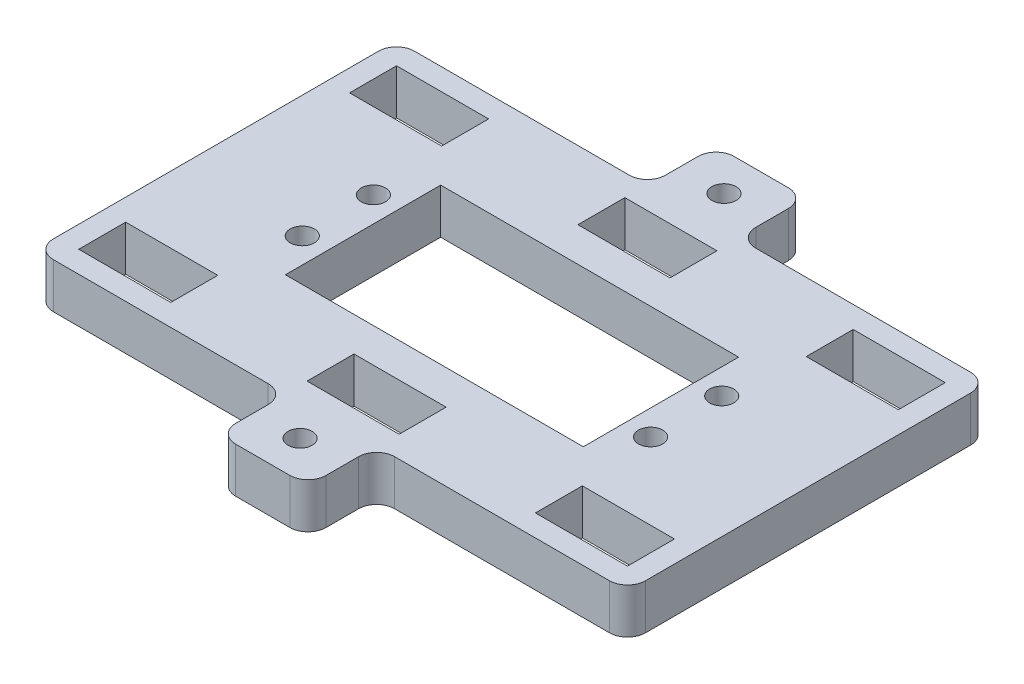
SolidWorks part; units mm, degrees
material "Acrylic (Medium-high impact)"
ref_plane "Front Plane" through (0, 0, 0) normal (0, 0, 1) x (1, 0, 0)
ref_plane "Top Plane" through (0, 0, 0) normal (0, 1, 0) x (1, 0, 0)
ref_plane "Right Plane" through (0, 0, 0) normal (1, 0, 0) x (0, 0, -1)
sketch "Sketch1" plane through (0, 0, 0) normal (0, 1, 0) x (1, 0, 0)
  line L0 (-25.7708, 22.225) -> (-6.35, 22.225) construction
  line L1 (-20.955, -10.922) -> (20.955, -10.922)
  line L2 (-20.955, -10.922) -> (-20.955, 10.922)
  line L3 (-20.955, 10.922) -> (20.955, 10.922)
  line L4 (20.955, -10.922) -> (20.955, 10.922)
  line L5 (-20.955, -10.922) -> (20.955, 10.922) construction
  line L6 (-20.955, 10.922) -> (20.955, -10.922) construction
  line L7 (24.4996, -5) -> (-24.4996, -5) construction
  line L8 (24.4996, -5) -> (24.4996, 5) construction
  line L9 (24.4996, 5) -> (-24.4996, 5) construction
  line L10 (-24.4996, -5) -> (-24.4996, 5) construction
  line L11 (24.4996, -5) -> (-24.4996, 5) construction
  line L12 (24.4996, 5) -> (-24.4996, -5) construction
  line L13 (41.6458, -25.4) -> (-41.6458, -25.4) construction
  line L14 (41.6458, -25.4) -> (41.6458, 25.4)
  line L15 (41.6458, 25.4) -> (-41.6458, 25.4) construction
  line L16 (-41.6458, -25.4) -> (-41.6458, 25.4)
  line L17 (41.6458, -25.4) -> (-41.6458, 25.4) construction
  line L18 (41.6458, 25.4) -> (-41.6458, -25.4) construction
  line L19 (-38.4708, 22.225) -> (-25.7708, 22.225) construction
  line L20 (-38.4708, 22.225) -> (-38.4708, 15.875) construction
  line L21 (-38.4708, 15.875) -> (-25.7708, 15.875) construction
  line L22 (-25.7708, 22.225) -> (-25.7708, 15.875) construction
  line L23 (-6.35, 22.225) -> (6.35, 22.225) construction
  line L24 (-6.35, 22.225) -> (-6.35, 15.875) construction
  line L25 (-6.35, 15.875) -> (6.35, 15.875) construction
  line L26 (6.35, 22.225) -> (6.35, 15.875) construction
  line L27 (25.7708, 22.225) -> (38.4708, 22.225) construction
  line L28 (25.7708, 22.225) -> (25.7708, 15.875) construction
  line L29 (25.7708, 15.875) -> (38.4708, 15.875) construction
  line L30 (38.4708, 22.225) -> (38.4708, 15.875) construction
  line L31 (6.35, 22.225) -> (25.7708, 22.225) construction
  line L32 (-41.6458, 0) -> (41.6458, 0) construction
  line L33 (38.4708, -22.225) -> (38.4708, -15.875) construction
  line L34 (25.7708, -15.875) -> (38.4708, -15.875) construction
  line L35 (25.7708, -22.225) -> (38.4708, -22.225) construction
  line L36 (25.7708, -22.225) -> (25.7708, -15.875) construction
  line L37 (6.35, -22.225) -> (6.35, -15.875) construction
  line L38 (-6.35, -15.875) -> (6.35, -15.875) construction
  line L39 (-6.35, -22.225) -> (6.35, -22.225) construction
  line L40 (-6.35, -22.225) -> (-6.35, -15.875) construction
  line L41 (-25.7708, -22.225) -> (-25.7708, -15.875) construction
  line L42 (-38.4708, -22.225) -> (-25.7708, -22.225) construction
  line L43 (-38.4708, -22.225) -> (-38.4708, -15.875) construction
  line L44 (-38.4708, -15.875) -> (-25.7708, -15.875) construction
  line L45 (0, -25.4) -> (0, -35.052) construction
  line L46 (-41.6458, -25.4) -> (-6.35, -25.4)
  line L47 (6.35, -25.4) -> (41.6458, -25.4)
  line L48 (-6.35, -25.4) -> (-6.35, -35.052)
  line L49 (-6.35, -35.052) -> (6.35, -35.052)
  line L50 (6.35, -25.4) -> (6.35, -35.052)
  line L51 (-38.5978, 22.352) -> (-38.5978, 15.748)
  line L52 (-38.5978, 15.748) -> (-25.6438, 15.748)
  line L53 (-25.6438, 22.352) -> (-25.6438, 15.748)
  line L54 (-38.5978, 22.352) -> (-25.6438, 22.352)
  line L55 (-6.477, 22.352) -> (-6.477, 15.748)
  line L56 (-6.477, 15.748) -> (6.477, 15.748)
  line L57 (6.477, 22.352) -> (6.477, 15.748)
  line L58 (-6.477, 22.352) -> (6.477, 22.352)
  line L59 (25.6438, 22.352) -> (25.6438, 15.748)
  line L60 (25.6438, 15.748) -> (38.5978, 15.748)
  line L61 (38.5978, 22.352) -> (38.5978, 15.748)
  line L62 (25.6438, 22.352) -> (38.5978, 22.352)
  line L63 (25.6438, -15.748) -> (38.5978, -15.748)
  line L64 (38.5978, -22.352) -> (38.5978, -15.748)
  line L65 (25.6438, -22.352) -> (38.5978, -22.352)
  line L66 (25.6438, -22.352) -> (25.6438, -15.748)
  line L67 (-6.477, -22.352) -> (-6.477, -15.748)
  line L68 (-6.477, -15.748) -> (6.477, -15.748)
  line L69 (6.477, -22.352) -> (6.477, -15.748)
  line L70 (-6.477, -22.352) -> (6.477, -22.352)
  line L71 (-25.6438, -22.352) -> (-25.6438, -15.748)
  line L72 (-38.5978, -15.748) -> (-25.6438, -15.748)
  line L73 (-38.5978, -22.352) -> (-38.5978, -15.748)
  line L74 (-38.5978, -22.352) -> (-25.6438, -22.352)
  line L75 (-41.6458, 25.4) -> (-6.35, 25.4)
  line L76 (6.35, 25.4) -> (41.6458, 25.4)
  line L77 (6.35, 25.4) -> (6.35, 35.052)
  line L78 (-6.35, 35.052) -> (6.35, 35.052)
  line L79 (-6.35, 25.4) -> (-6.35, 35.052)
  circle A0 centre (-24.4996, 5) radius 1.7005
  circle A1 centre (-24.4996, -5) radius 1.7005
  circle A2 centre (24.4996, -5) radius 1.7005
  circle A3 centre (24.4996, 5) radius 1.7005
  circle A4 centre (0, -29.8145) radius 1.7005
  circle A5 centre (0, 29.8145) radius 1.7005
  point P0 (0, 0)
  point P6 (0, 0)
  point P11 (0, 0)
  dimension "D7" = 3.4011
  dimension "D1" = 41.91
  dimension "D2" = 21.844
  dimension "D3" = 48.9991
  dimension "D4" = 10
  dimension "D5" = 83.2917
  dimension "D6" = 50.8
  dimension "D8" = 12.7
  dimension "D9" = 3.175
  dimension "D10" = 6.35
  dimension "D11" = 3.175
  dimension "D12" = 3.175
  dimension "D13" = 12.7
  dimension "D14" = 12.7
  dimension "D16" = 5.2375
  dimension "D15" = 0.127
extrude "Boss-Extrude1" add sketch "Sketch1" along normal blind 6.35
fillet "Fillet2" radius 2.54 12 edges at (6.35, 3.175, -35.052) (6.35, 3.175, -25.4) (41.6458, 3.175, -25.4) (-6.35, 3.175, -35.052) (-6.35, 3.175, -25.4) (-41.6458, 3.175, -25.4) (-41.6458, 3.175, 25.4) (41.6458, 3.175, 25.4) (6.35, 3.175, 25.4) (6.35, 3.175, 35.052) (-6.35, 3.175, 35.052) (-6.35, 3.175, 25.4)
